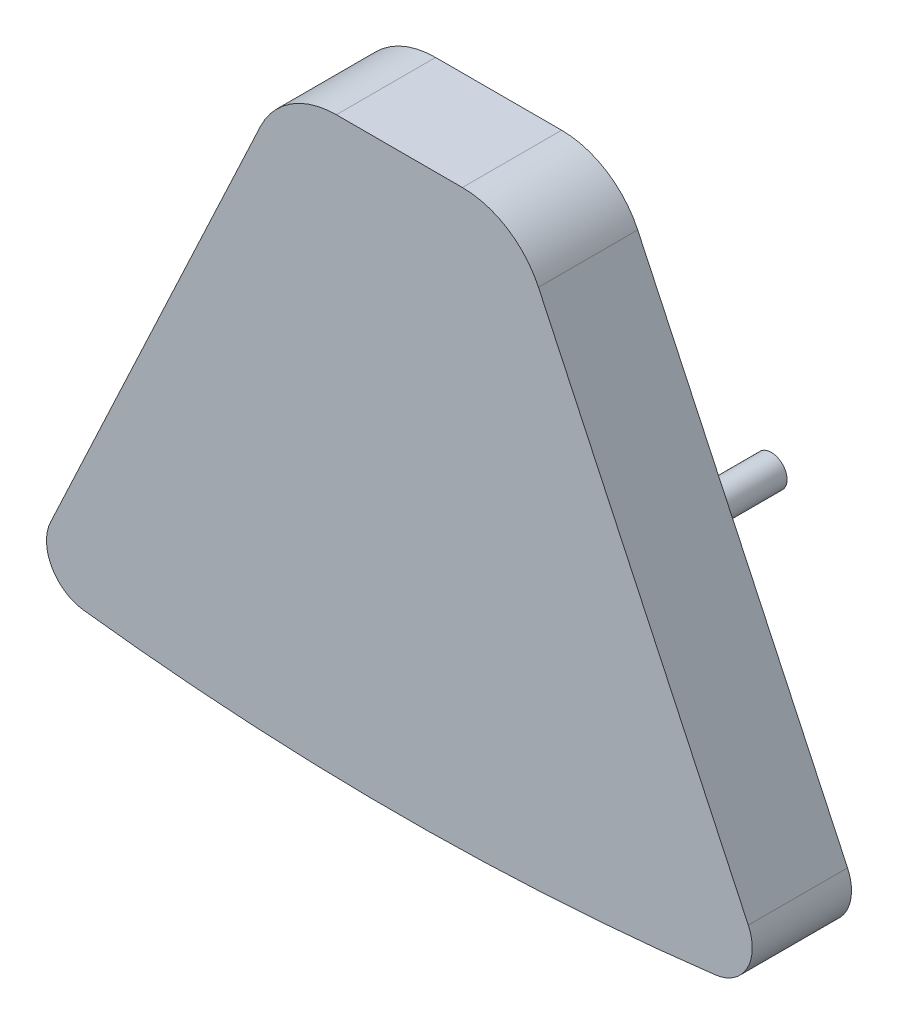
SolidWorks part; units mm, degrees
ref_plane "Front Plane" through (0, 0, 0) normal (0, 0, 1) x (1, 0, 0)
ref_plane "Top Plane" through (0, 0, 0) normal (0, 1, 0) x (1, 0, 0)
ref_plane "Right Plane" through (0, 0, 0) normal (1, 0, 0) x (0, 0, -1)
sketch "Sketch1" plane through (0, 0, 0) normal (0, 0, 1) x (1, 0, 0)
  line L0 (-52.7394, 11.9161) -> (-21.0238, 79.5594)
  line L1 (-9.525, 86.868) -> (9.525, 86.868)
  line L4 (0, 73.0285) -> (0, 24.2987) construction
  line L5 (52.7394, 11.9161) -> (21.0238, 79.5594)
  arc A0 (-47.7629, 2.9177) -> (47.7629, 2.9177) centre (0, 392.4049) ccw
  arc A1 (52.7394, 11.9161) -> (47.7629, 2.9177) centre (46.99, 9.2204) cw
  arc A2 (-52.7394, 11.9161) -> (-47.7629, 2.9177) centre (-46.99, 9.2204) ccw
  arc A3 (21.0238, 79.5594) -> (9.525, 86.868) centre (9.525, 74.168) ccw
  arc A4 (-21.0238, 79.5594) -> (-9.525, 86.868) centre (-9.525, 74.168) cw
  point P4 (0, 0)
  point P8 (0, 0)
  point P9 (0, 86.868)
  point P14 (56.4151, 4.0765)
  point P17 (-56.4151, 4.0765)
  point P20 (17.5971, 86.868)
  point P23 (-17.5971, 86.868)
  dimension "D3" = 6.35
  dimension "D4" = 12.7
  dimension "D6" = 106.68
  dimension "D1" = 19.05
  dimension "D2" = 91.44
  dimension "D5" = 86.868
extrude "Boss-Extrude1" add sketch "Sketch1" along normal blind 15 contours L5 A3 L1 A4 L0 A2 A0 A1
sketch "Sketch2" plane through (0, 0, 0) normal (0, 0, -1) x (-1, 0, 0)
  line L0 (-27.5, 44.45) -> (27.5, 44.45) construction
  line L1 (0, 0) -> (0, 44.45) construction
  circle A0 centre (-27.5, 44.45) radius 2.3812
  circle A1 centre (27.5, 44.45) radius 2.3813
  dimension "D1" = 4.7625
  dimension "D2" = 55
  dimension "D3" = 44.45
extrude "Boss-Extrude2" add sketch "Sketch2" along normal blind 13.716
